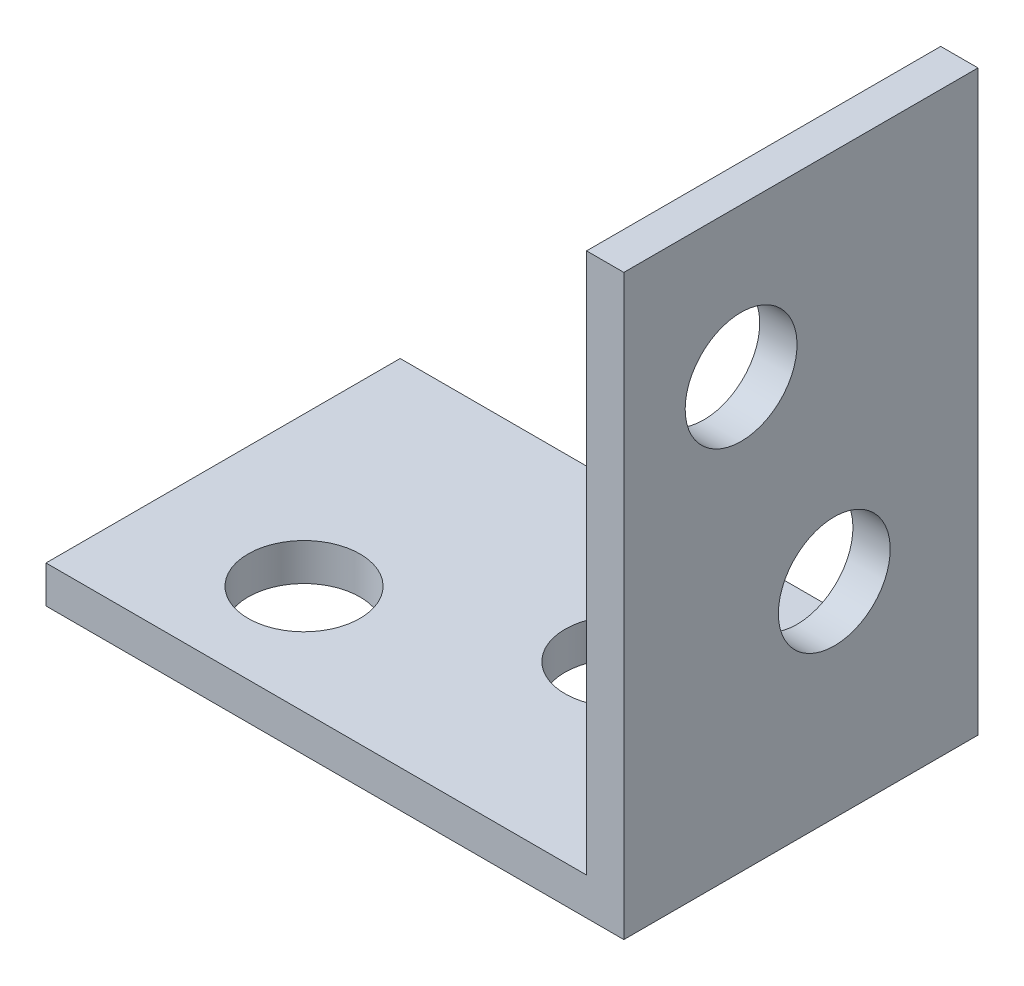
SolidWorks part; units mm, degrees
ref_plane "前视基准面" through (0, 0, 0) normal (0, 0, 1) x (1, 0, 0)
ref_plane "上视基准面" through (0, 0, 0) normal (0, 1, 0) x (1, 0, 0)
ref_plane "右视基准面" through (0, 0, 0) normal (1, 0, 0) x (0, 0, -1)
other "Configuration Table"
sketch "草图1" plane through (0, 0, 0) normal (0, 0, 1) x (1, 0, 0)
  line L0 (0, 0) -> (31, 0)
  line L1 (31, 0) -> (31, 31)
  line L2 (31, 31) -> (29, 31)
  line L3 (29, 31) -> (29, 2)
  line L4 (29, 2) -> (0, 2)
  line L5 (0, 2) -> (0, 0)
  dimension "D1" = 2
  dimension "D2" = 2
  dimension "D3" = 31
  dimension "D4" = 31
extrude "凸台-拉伸1" add sketch "草图1" along normal blind 19
sketch "草图2" plane through (29, 0, 0) normal (-1, 0, 0) x (0, 0, 1)
  line L0 (19, 31) -> (0, 31) construction
  circle A0 centre (7.7098, 11) radius 3
  circle A1 centre (12.7098, 23) radius 3
  dimension "D1" = 6
  dimension "D2" = 6
  dimension "D3" = 8
  dimension "D4" = 12
  dimension "D5" = 5
extrude "切除-拉伸1" cut sketch "草图2" against normal blind 19
sketch "草图3" plane through (0, 2, 0) normal (0, 1, 0) x (1, 0, 0)
  line L0 (0, -19) -> (0, 0) construction
  circle A0 centre (20, -8.1569) radius 3
  circle A1 centre (8, -13.1569) radius 3
  point P8 (3.7018, -8.8456)
  dimension "D1" = 6
  dimension "D2" = 6
  dimension "D3" = 8
  dimension "D4" = 5
  dimension "D5" = 12
extrude "切除-拉伸2" cut sketch "草图3" against normal blind 19
